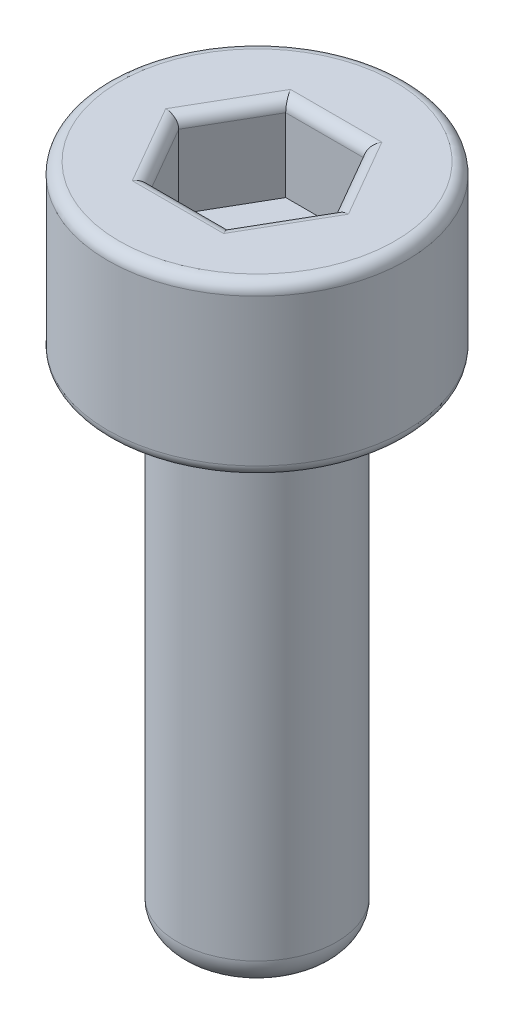
SolidWorks part; units mm, degrees
ref_plane "Front Plane" through (0, 0, 0) normal (0, 0, 1) x (1, 0, 0)
ref_plane "Top Plane" through (0, 0, 0) normal (0, 1, 0) x (1, 0, 0)
ref_plane "Right Plane" through (0, 0, 0) normal (1, 0, 0) x (0, 0, -1)
sketch "Sketch1" plane through (0, 0, 0) normal (0, 1, 0) x (1, 0, 0)
  circle A0 centre (0, 0) radius 2.64
  dimension "D1" = 5.28
extrude "Boss-Extrude1" add sketch "Sketch1" along normal blind 3
sketch "Sketch2" plane through (0, 0, 0) normal (0, -1, 0) x (1, 0, 0)
  circle A0 centre (0, 0) radius 1.405
  dimension "D1" = 2.81
extrude "Boss-Extrude2" add sketch "Sketch2" along normal blind 8.76
fillet "Fillet1" radius 0.2 2 edges at (0, 3, 2.64) (0, 0, 2.64)
sketch "Sketch3" plane through (0, 3, 0) normal (0, 1, 0) x (1, 0, 0)
  line L1 (1.3856, 0) -> (0.6928, 1.2)
  line L2 (0.6928, 1.2) -> (-0.6928, 1.2)
  line L3 (-0.6928, 1.2) -> (-1.3856, 0)
  line L4 (-1.3856, 0) -> (-0.6928, -1.2)
  line L5 (-0.6928, -1.2) -> (0.6928, -1.2)
  line L6 (0.6928, -1.2) -> (1.3856, 0)
  circle A0 centre (0, 0) radius 1.2 construction
  dimension "D1" = 2.4
extrude "Cut-Extrude1" cut sketch "Sketch3" against normal blind 1.5
fillet "Fillet2" radius 0.2 6 edges at (1.0392, 3, -0.6) (0, 3, -1.2) (-1.0392, 3, -0.6) (-1.0392, 3, 0.6) (0, 3, 1.2) (1.0392, 3, 0.6)
fillet "Fillet3" radius 0.5 1 edges at (0, -8.76, -1.405)
